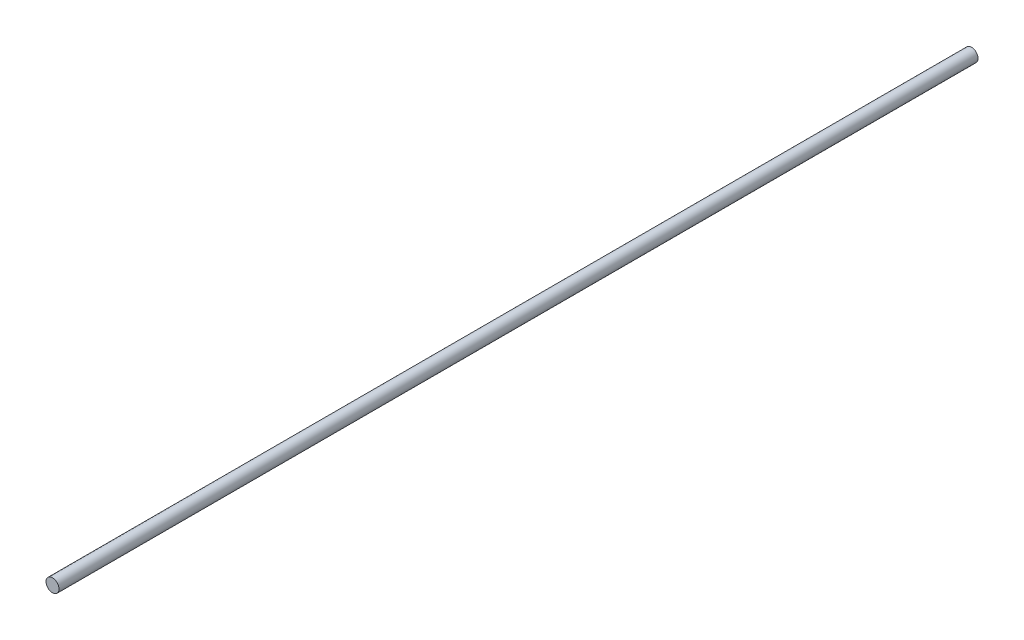
SolidWorks part; units mm, degrees
material "1060 Alloy"
ref_plane "Front Plane" through (0, 0, 0) normal (0, 0, 1) x (1, 0, 0)
ref_plane "Top Plane" through (0, 0, 0) normal (0, 1, 0) x (1, 0, 0)
ref_plane "Right Plane" through (0, 0, 0) normal (1, 0, 0) x (0, 0, -1)
sketch "Sketch4" plane through (0, 0, 0) normal (0, 0, 1) x (1, 0, 0)
  circle A0 centre (0, 0) radius 6.35
  dimension "D1" = 12.7
extrude "Boss-Extrude1" add sketch "Sketch4" along normal blind 898.3948
equation "\"d\"= 0.5'diameter of the bar [in]"
equation "\"Area\"= 3.1416 * \"d\" * \"d\" / 4'cross sectional area [in^2]"
equation "\"F\"= 500'load [lbf]"
equation "\"def\" = 0.009'max deflection [in]"
equation "\"E\"= 10007603.9'Youngs mod of Al [psi]"
equation "\"L\"= \"def\" * \"Area\" * \"E\" / \"F\"'Designed length"
equation "\"D1@Sketch4\"=\"d\""
equation "\"D1@Boss-Extrude1\"=\"L\""
